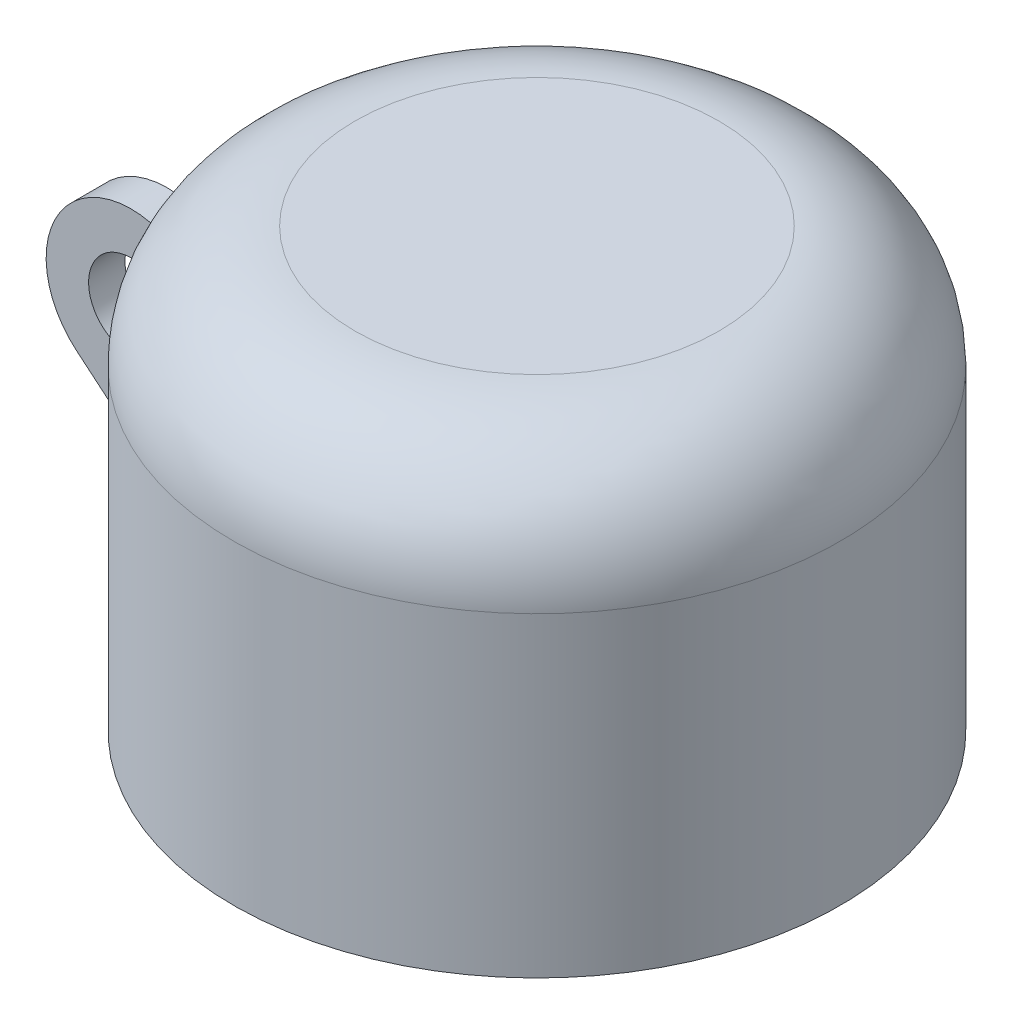
SolidWorks part; units mm, degrees
ref_plane "Front Plane" through (0, 0, 0) normal (0, 0, 1) x (1, 0, 0)
ref_plane "Top Plane" through (0, 0, 0) normal (0, 1, 0) x (1, 0, 0)
ref_plane "Right Plane" through (0, 0, 0) normal (1, 0, 0) x (0, 0, -1)
sketch "Sketch1" plane through (0, 0, 0) normal (0, 0, 1) x (1, 0, 0)
  line L0 (0, 0) -> (25, 0)
  line L1 (25, 0) -> (25, 26)
  line L2 (15, 36) -> (0, 36)
  line L3 (0, 36) -> (0, 0) construction
  line L4 (1, 1) -> (24, 1)
  line L5 (24, 1) -> (24, 26)
  line L6 (15, 35) -> (1, 35)
  line L7 (1, 35) -> (1, 1) construction
  line L8 (0, 36) -> (0, 35)
  line L9 (0, 35) -> (1, 35)
  line L10 (0, 0) -> (0, 1)
  line L11 (0, 1) -> (1, 1)
  arc A0 (25, 26) -> (15, 36) centre (15, 26) ccw
  arc A1 (24, 26) -> (15, 35) centre (15, 26) ccw
  point P7 (25, 36)
  dimension "D3" = 10
  dimension "D1" = 25
  dimension "D2" = 36
  dimension "D4" = 1
revolve "Revolve1" add sketch "Sketch1" angle 360 about L3
ref_plane "Plane2" through (-25, 0, 0) normal (-1, 0, 0) x (0, 0, 1)
sketch "Sketch5" plane through (-25, 0, 0) normal (-1, 0, 0) x (0, 0, 1)
  line L0 (25, 26) -> (-25, 26) construction
  line L1 (-1.5, 26) -> (1.5, 26)
  line L2 (-1.5, 26) -> (-1.5, 0)
  line L3 (-1.5, 0) -> (1.5, 0)
  line L4 (1.5, 26) -> (1.5, 0)
  line L5 (-25, 0) -> (25, 0) construction
  dimension "D1" = 1.5
  dimension "D2" = 3
extrude "Boss-Extrude1" add sketch "Sketch5" along normal blind 15 and the other way up to surface other way up to face at (-25, 26, 0)
sketch "Sketch4" plane through (0, 0, 0) normal (0, 0, 1) x (1, 0, 0)
  line L2 (-24.955, 0) -> (-36.4513, 9.635)
  line L4 (-24.955, 0) -> (25, 0) construction
  line L6 (-24.955, 26) -> (-24.955, 15)
  line L7 (-24.955, 26) -> (-40, 26)
  line L8 (-40, 26) -> (-40, 0)
  line L9 (-40, 0) -> (-24.955, 0)
  line L10 (-24.955, 15) -> (-24.955, 0) construction
  arc A0 (-24.955, 15) -> (-36.4513, 9.635) centre (-31.955, 15) ccw
  circle A1 centre (-31.955, 15) radius 3.5
  point P1 (0, 0)
  dimension "D1" = 7
  dimension "D2" = 7
  dimension "D3" = 15
extrude "Cut-Extrude1" cut sketch "Sketch4" against normal through all both and the other way through all
